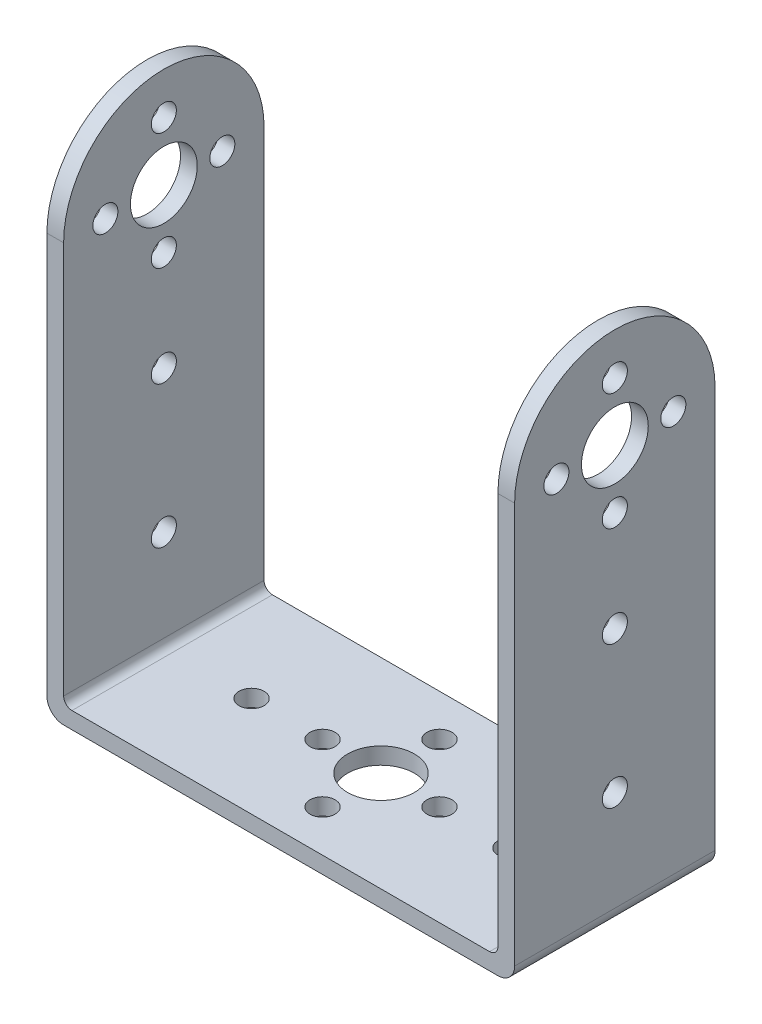
SolidWorks part; units mm, degrees
ref_plane "Front Plane" through (0, 0, 0) normal (0, 0, 1) x (1, 0, 0)
ref_plane "Top Plane" through (0, 0, 0) normal (0, 1, 0) x (1, 0, 0)
ref_plane "Right Plane" through (0, 0, 0) normal (1, 0, 0) x (0, 0, -1)
sketch "Sketch1" plane through (0, 0, 0) normal (0, 1, 0) x (1, 0, 0)
  line L1 (-26, -12) -> (26, -12)
  line L2 (-26, -12) -> (-26, 12)
  line L3 (-26, 12) -> (26, 12)
  line L4 (26, -12) -> (26, 12)
  line L5 (-26, -12) -> (26, 12) construction
  line L6 (-26, 12) -> (26, -12) construction
  circle A0 centre (0, 0) radius 7 construction
  circle A1 centre (0, 0) radius 4
  circle A2 centre (0, 7) radius 1.5
  circle A3 centre (0, -7) radius 1.5
  circle A4 centre (7, 0) radius 1.5
  circle A5 centre (-7, 0) radius 1.5
  circle A6 centre (-15.5, 0) radius 1.5
  circle A7 centre (15.5, 0) radius 1.5
  point P0 (0, 0)
  dimension "D3" = 14
  dimension "D4" = 8
  dimension "D5" = 3
  dimension "D6" = 3
  dimension "D7" = 3
  dimension "D8" = 3
  dimension "D9" = 3
  dimension "D10" = 3
  dimension "D1" = 52
  dimension "D2" = 24
  dimension "D11" = 31
  dimension "D12" = 8.5
  dimension "D13" = 8.5
extrude "Boss-Extrude1" add sketch "Sketch1" along normal blind 2
sketch "Sketch3" plane through (26, 0, 0) normal (1, 0, 0) x (0, 0, -1)
  line L0 (-12, 0) -> (12, 0)
  line L1 (-12, 0) -> (-12, 50)
  line L2 (12, 0) -> (12, 50)
  arc A0 (-12, 50) -> (12, 50) centre (0, 50) cw
  circle A1 centre (0, 50) radius 7 construction
  circle A2 centre (0, 50) radius 4
  circle A3 centre (0, 57) radius 1.5
  circle A4 centre (7, 50) radius 1.5
  circle A5 centre (0, 43) radius 1.5
  circle A6 centre (-7, 50) radius 1.5
  circle A10 centre (0, 31) radius 1.5
  circle A11 centre (0, 14) radius 1.5
  point P8 (0, 62)
  dimension "D2" = 8
  dimension "D3" = 14
  dimension "D4" = 3
  dimension "D1" = 62
  dimension "D5" = 12
  dimension "D6" = 17
extrude "Boss-Extrude2" add sketch "Sketch3" along normal blind 2
fillet "Fillet1" radius 2 1 edges at (28, 0, 0)
fillet "Fillet2" radius 1 1 edges at (26, 2, 0)
sketch "Sketch5" plane through (-26, 0, 0) normal (-1, 0, 0) x (0, 0, 1)
  line L0 (-12, 0) -> (-12, 50)
  line L1 (12, 50) -> (12, 0)
  line L2 (12, 0) -> (-12, 0)
  line L3 (0, 31) -> (0, 43) construction
  line L4 (0, 31) -> (0, 14) construction
  arc A0 (-12, 50) -> (12, 50) centre (0, 50) cw
  circle A1 centre (0, 50) radius 4
  circle A2 centre (0, 57) radius 1.5
  circle A3 centre (0, 43) radius 1.5
  circle A4 centre (7, 50) radius 1.5
  circle A5 centre (-7, 50) radius 1.5
  circle A9 centre (0, 31) radius 1.5
  circle A10 centre (0, 14) radius 1.5
  dimension "D1" = 8
  dimension "D2" = 3
  dimension "D3" = 12
  dimension "D4" = 17
extrude "Boss-Extrude3" add sketch "Sketch5" along normal blind 2
fillet "Fillet3" radius 2 1 edges at (-28, 0, 0)
fillet "Fillet4" radius 1 1 edges at (-26, 2, 0)
